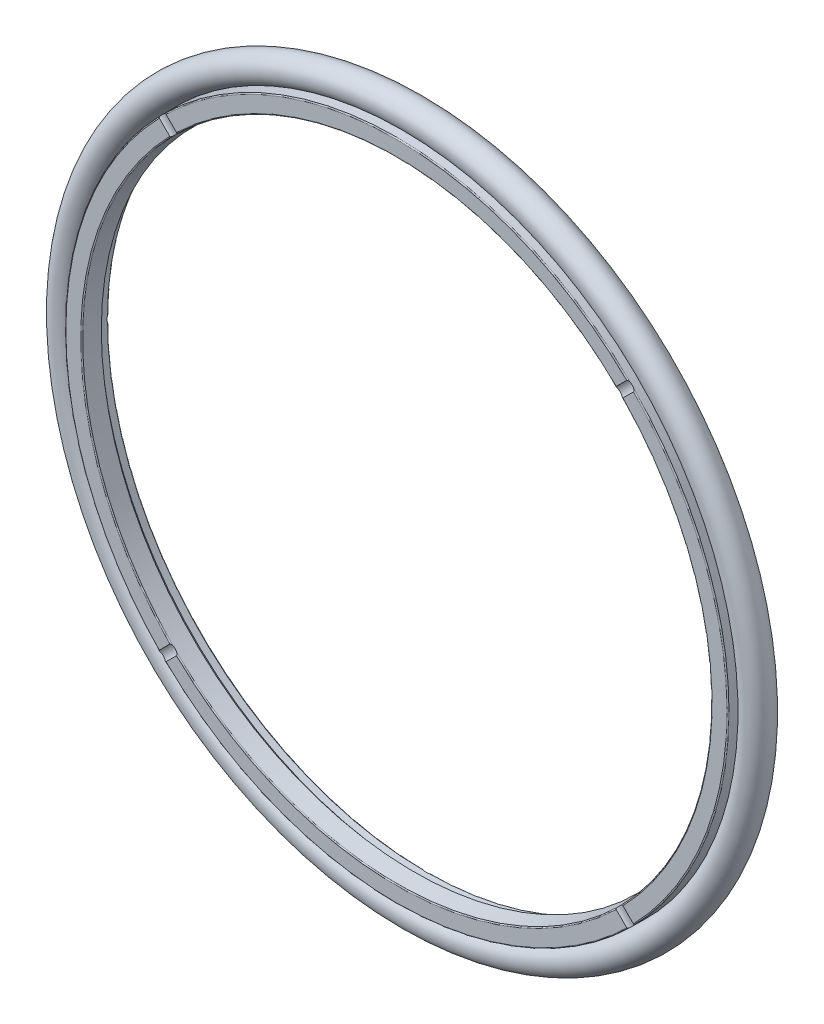
SolidWorks part; units mm, degrees
material "PTFE+NBR"
ref_plane "Front Plane" through (0, 0, 0) normal (0, 0, 1) x (1, 0, 0)
ref_plane "Top Plane" through (0, 0, 0) normal (0, 1, 0) x (1, 0, 0)
ref_plane "Right Plane" through (0, 0, 0) normal (1, 0, 0) x (0, 0, -1)
sketch "Sketch1" plane through (0, 0, 0) normal (1, 0, 0) x (0, 0, -1)
  line L0 (0, 61) -> (0, 62.95)
  line L1 (-0.2, 63.15) -> (-5.75, 63.15)
  line L2 (-5.95, 62.95) -> (-5.95, 60.1334)
  line L3 (-5.7673, 59.9341) -> (-2.5, 59.65)
  line L5 (-1.5, 60.8) -> (-2.5, 59.65)
  line L6 (0, 0) -> (-16.4728, 0) construction
  line L7 (-0.2, 60.8) -> (-1.5, 60.8)
  arc A0 (-0.2, 63.15) -> (0, 62.95) centre (-0.2, 62.95) cw
  arc A1 (0, 61) -> (-0.2, 60.8) centre (-0.2, 61) cw
  arc A2 (-5.95, 62.95) -> (-5.75, 63.15) centre (-5.75, 62.95) cw
  arc A3 (-5.95, 60.1334) -> (-5.7673, 59.9341) centre (-5.75, 60.1334) ccw
  point P13 (-5.95, 63.15)
  point P19 (-5.95, 59.95)
  dimension "D2" = 0.2
  dimension "D4" = 3.5
  dimension "D10" = 2.5
  dimension "D11" = 0.2
  dimension "D13" = 0.2
  dimension "D1" = 5.95
  dimension "D3" = 119.3
  dimension "D5" = 2.35
  dimension "D6" = 3.2
  dimension "D7" = 1.5
  dimension "D8" = 126.3
  dimension "D9" = 119.9
  dimension "D12" = 121.6
revolve "Revolve1" add sketch "Sketch1" angle 360 about L6
sketch "Sketch4" plane through (0, 0, 0) normal (1, 0, 0) x (0, 0, -1)
  line L0 (0, 0) -> (-5.95, 0) construction
  line L2 (-2.975, 0) -> (-2.975, 52.8756) construction
  line L3 (-5.95, 63.15) -> (-5.95, -63.15) construction
  circle A0 centre (-2.975, 65.85) radius 2.665
  dimension "D1" = 126.37
  dimension "D2" = 5.33
revolve "Revolve2" add sketch "Sketch4" angle 360 about L0
sketch "Sketch2" plane through (0, 0, 0) normal (1, 0, 0) x (0, 0, -1)
  line L0 (0, 0) -> (14.1525, 0) construction
  line L1 (0, -62.95) -> (0, 62.95) construction
  line L2 (0, 0.9) -> (0, -0.9)
  arc A0 (0, 0.9) -> (0, -0.9) centre (1.495, 0) ccw
  dimension "D1" = 0.25
  dimension "D2" = 1.8
extrude "Cut-Extrude1" cut sketch "Sketch2" against normal through all and the other way through all
ref_axis "Axis1" through (0, 0, 0) along (0, 0, 1)
pattern_circular "CirPattern1" count 4 over 360 about axis through (0, 0, 0) along (0, 0, 1) of "Cut-Extrude1"
ref_plane "Plane1" through (0, 0, 0) normal (0.7071, -0.7071, 0) x (0.7071, 0.7071, 0)
sketch "Sketch3" plane through (0, 0, 0) normal (0.7071, -0.7071, 0) x (0.7071, 0.7071, 0)
  line L0 (0, 0) -> (0, 13.0703) construction
  line L1 (-0.9, 5.95) -> (0.9, 5.95)
  line L3 (63.15, 5.95) -> (-63.15, 5.95) construction
  arc A0 (-0.9, 5.95) -> (0.9, 5.95) centre (0, 7.445) ccw
  dimension "D1" = 0.25
  dimension "D2" = 1.8
extrude "Cut-Extrude2" cut sketch "Sketch3" against normal through all and the other way through all
pattern_circular "CirPattern2" count 4 over 360 about axis through (0, 0, 0) along (0, 0, 1) of "Cut-Extrude2"
